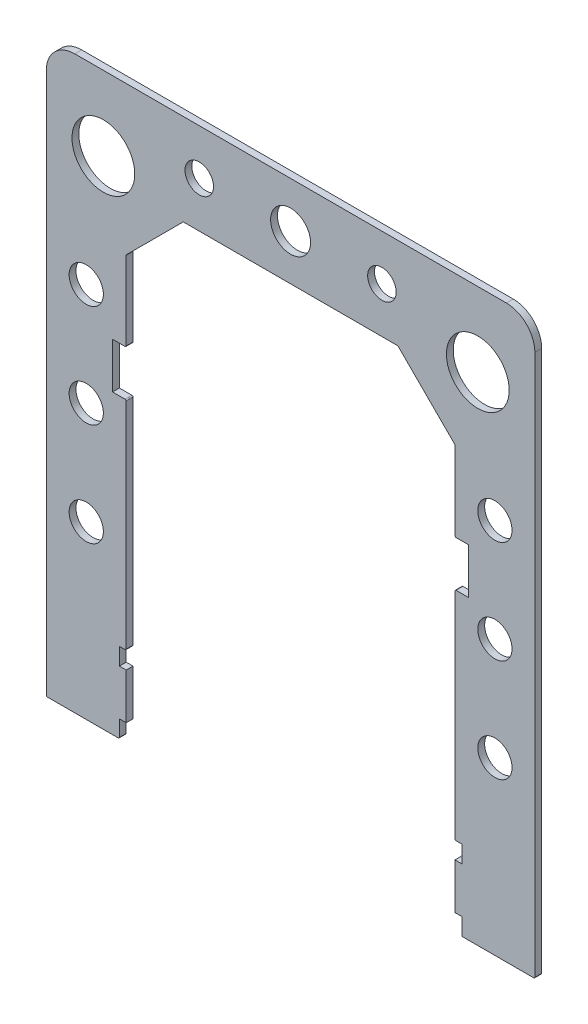
SolidWorks part; units mm, degrees
material "Beech"
ref_plane "Спереди" through (0, 0, 0) normal (0, 0, 1) x (1, 0, 0)
ref_plane "Сверху" through (0, 0, 0) normal (0, 1, 0) x (1, 0, 0)
ref_plane "Справа" through (0, 0, 0) normal (1, 0, 0) x (0, 0, -1)
sketch "Sketch1" plane through (0, 0, 0) normal (0, 0, 1) x (1, 0, 0)
  line L0 (0, 0) -> (-70, 0)
  line L1 (-70, 0) -> (-70, 500)
  line L2 (-70, 500) -> (358, 500)
  line L3 (358, 500) -> (358, 0)
  line L4 (358, 0) -> (288, 0)
  line L5 (288, 0) -> (288, 370)
  line L6 (238, 420) -> (50, 420)
  line L7 (0, 370) -> (0, 0)
  line L8 (50, 420) -> (0, 370)
  line L9 (288, 370) -> (238, 420)
  point P8 (288, 420)
  point P9 (0, 420)
  dimension "D1" = 70
  dimension "D2" = 70
  dimension "D3" = 288
  dimension "D4" = 500
  dimension "D5" = 80
  dimension "D8" = 50
  dimension "D9" = 50
extrude "tower" add sketch "Sketch1" against normal blind 6
sketch "Sketch2" plane through (0, 0, 0) normal (0, 0, 1) x (1, 0, 0)
  line L0 (0, 70) -> (-6, 70)
  line L1 (0, 0) -> (0, 370) construction
  line L2 (-6, 70) -> (-6, 55)
  line L3 (-6, 55) -> (0, 55)
  line L4 (0, 55) -> (0, 70)
  line L5 (0, 15) -> (-6, 15)
  line L6 (-6, 15) -> (-6, 0)
  line L7 (-70, 0) -> (0, 0) construction
  line L8 (-6, 0) -> (0, 0)
  line L9 (0, 0) -> (0, 15)
  line L10 (288, 15) -> (294, 15)
  line L11 (288, 370) -> (288, 0) construction
  line L12 (294, 15) -> (294, 0)
  line L13 (288, 0) -> (358, 0) construction
  line L14 (294, 0) -> (288, 0)
  line L15 (288, 0) -> (288, 15)
  line L16 (288, 55) -> (294, 55)
  line L17 (294, 55) -> (294, 70)
  line L18 (294, 70) -> (288, 70)
  line L19 (288, 70) -> (288, 55)
  line L20 (0, 300) -> (-12, 300)
  line L21 (0, 0) -> (0, 370) construction
  line L22 (-12, 300) -> (-12, 260)
  line L23 (-12, 260) -> (0, 260)
  line L24 (0, 260) -> (0, 300)
  line L25 (288, 300) -> (300, 300)
  line L26 (288, 370) -> (288, 0) construction
  line L27 (300, 300) -> (300, 260)
  line L28 (300, 260) -> (288, 260)
  line L29 (288, 260) -> (288, 300)
  dimension "D1" = 40
  dimension "D2" = 70
  dimension "D3" = 6
  dimension "D4" = 40
  dimension "D5" = 260
  dimension "D6" = 12
extrude "mount" cut sketch "Sketch2" against normal through all contours L2 L3 L4 L0 | L6 L8 L9 L5 | L17 L18 L19 L16 | L12 L14 L15 L10 | L24 L20 L22 L23 | L27 L28 L29 L25
fillet "fillet" radius 1 14 edges at (288, 70, -3) (-6, 0, -3) (358, 0, -3) (294, 0, -3) (0, 70, -3) (-70, 0, -3) (288, 370, -3) (238, 420, -3) (50, 420, -3) (0, 370, -3) (288, 260, -3) (288, 300, -3) (0, 260, -3) (0, 300, -3)
sketch "Sketch3" plane through (0, 0, 0) normal (0, 0, 1) x (1, 0, 0)
  line L0 (64, 460) -> (144, 460) construction
  line L1 (144, 460) -> (224, 460) construction
  line L2 (358, 500) -> (-70, 500) construction
  line L3 (50.4142, 420) -> (237.5858, 420) construction
  line L4 (-70, 500) -> (-70, 1) construction
  line L5 (358, 1) -> (358, 500) construction
  line L6 (-69, 0) -> (-7, 0) construction
  circle A0 centre (64, 460) radius 12.5
  circle A1 centre (144, 460) radius 17.5
  circle A2 centre (224, 460) radius 12.5
  circle A3 centre (-20, 435) radius 27.5
  circle A4 centre (308, 435) radius 27.5
  circle A5 centre (-35, 330) radius 15
  circle A6 centre (-35, 240) radius 15
  circle A7 centre (-35, 150) radius 15
  circle A8 centre (323, 330) radius 15
  circle A9 centre (323, 240) radius 15
  circle A10 centre (323, 150) radius 15
  point P10 (144, 500)
  dimension "D1" = 25
  dimension "D4" = 65
  dimension "D5" = 55
  dimension "D6" = 50
  dimension "D7" = 50
  dimension "D8" = 35
  dimension "D9" = 30
  dimension "D10" = 35
  dimension "D11" = 35
  dimension "D13" = 90
  dimension "D14" = 90
  dimension "D2" = 80
  dimension "D3" = 40
  dimension "D12" = 150
extrude "lite" cut sketch "Sketch3" against normal through all
fillet "fillet2" radius 25 2 edges at (358, 500, -3) (-70, 500, -3)
